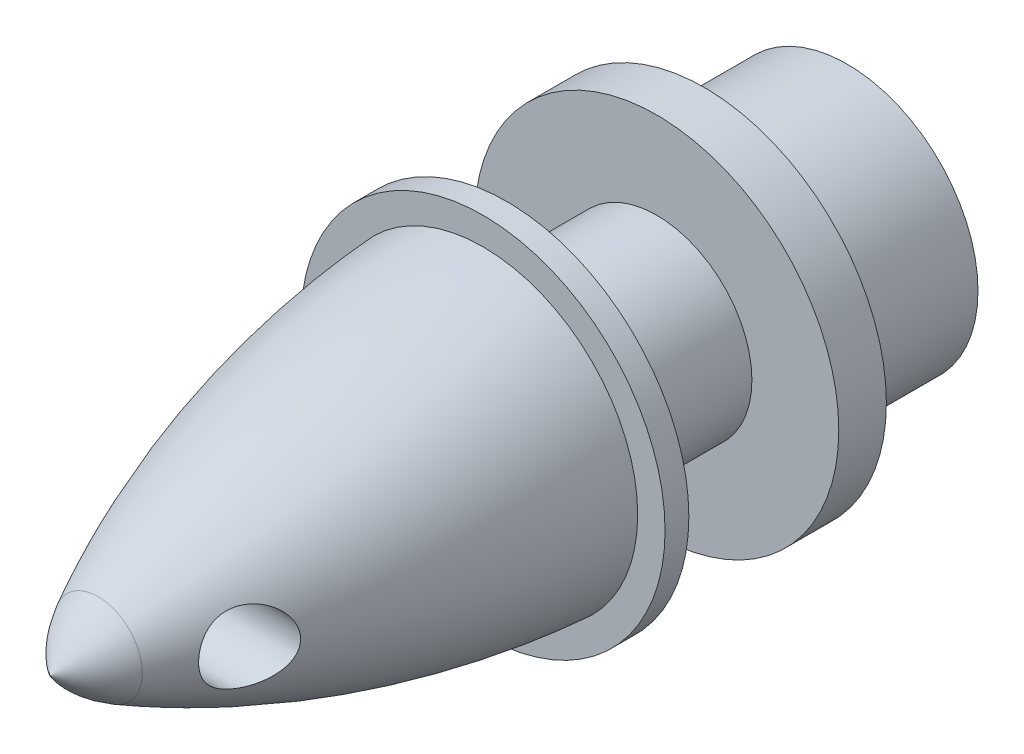
SolidWorks part; units mm, degrees
ref_plane "Спереди" through (0, 0, 0) normal (0, 0, 1) x (1, 0, 0)
ref_plane "Сверху" through (0, 0, 0) normal (0, 1, 0) x (1, 0, 0)
ref_plane "Справа" through (0, 0, 0) normal (1, 0, 0) x (0, 0, -1)
sketch "Эскиз1" plane through (0, 0, 0) normal (1, 0, 0) x (0, 0, -1)
  line L0 (-16.75, 0) -> (16.75, 0)
  line L1 (16.75, 0) -> (33.8011, 0) construction
  line L2 (16.75, 0) -> (16.75, 5.5)
  line L3 (16.75, 5.5) -> (11.95, 5.5)
  line L4 (11.95, 5.5) -> (10.75, 7.65)
  line L5 (10.75, 7.65) -> (8.75, 7.65)
  line L6 (8.75, 7.65) -> (8.75, 4)
  line L7 (8.75, 4) -> (2.45, 4)
  line L8 (2.45, 4) -> (2.45, 7.65)
  line L9 (2.45, 7.65) -> (1.45, 7.65)
  line L10 (1.45, 7.65) -> (1.45, 6.5)
  arc A0 (-16.75, 0) -> (-14.7233, 1.8557) centre (-12.1402, -3) cw
  arc A1 (-14.7233, 1.8557) -> (1.45, 6.5) centre (4.2977, -33.8998) cw
  point P16 (-14.3549, -2.3303)
  point P17 (0, 0)
  point P18 (7.848, 4)
  point P19 (-15.3338, 1.4778)
  dimension "D1" = 5.5
  dimension "D13" = 40.5
  dimension "D2" = 3
  dimension "D3" = 1
  dimension "D4" = 2
  dimension "D5" = 6.3
  dimension "D6" = 4.8
  dimension "D7" = 8
  dimension "D8" = 11
  dimension "D9" = 15.3
  dimension "D10" = 1.15
  dimension "D11" = 15.3
  dimension "D12" = 33.5
revolve "Повернуть1" add sketch "Эскиз1" angle 360 about L1
ref_plane "Плоскость1" through (7.65, 0, 0) normal (1, 0, 0) x (0, 0, -1)
sketch "Эскиз2" plane through (7.65, 0, 0) normal (1, 0, 0) x (0, 0, -1)
  line L0 (16.75, -5.5) -> (16.75, 5.5) construction
  circle A0 centre (-11.65, 0) radius 1.5
  dimension "D1" = 3
  dimension "D2" = 28.4
extrude "Вырез-Вытянуть1" cut sketch "Эскиз2" against normal through all
